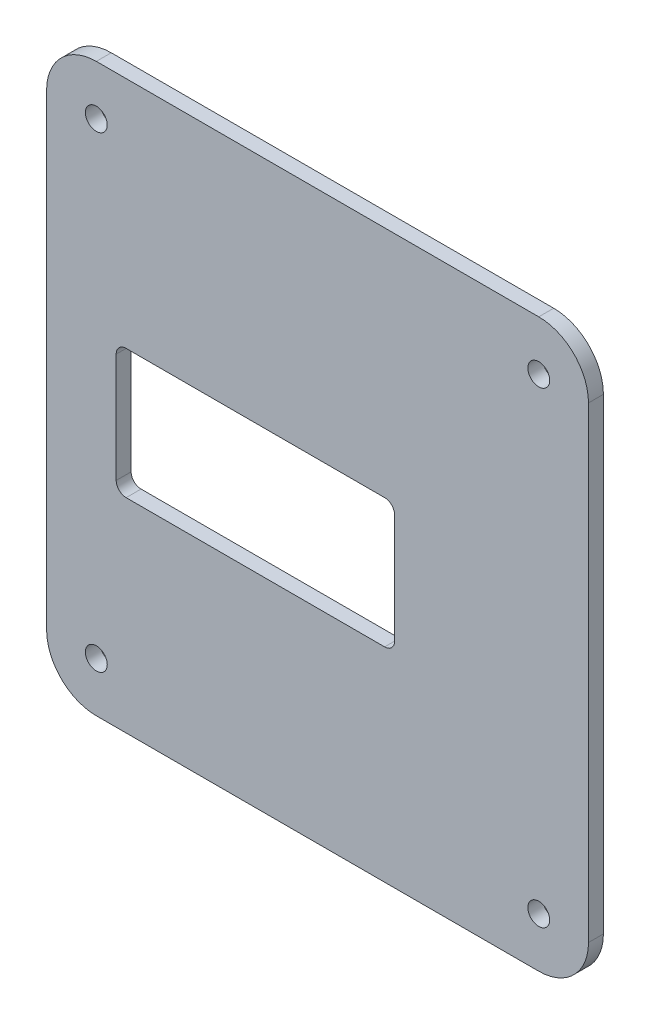
SolidWorks part; units mm, degrees
ref_plane "前视基准面" through (0, 0, 0) normal (0, 0, 1) x (1, 0, 0)
ref_plane "上视基准面" through (0, 0, 0) normal (0, 1, 0) x (1, 0, 0)
ref_plane "右视基准面" through (0, 0, 0) normal (1, 0, 0) x (0, 0, -1)
sketch "草图1" plane through (0, 0, 0) normal (0, 0, 1) x (1, 0, 0)
  line L1 (0, 0) -> (109, 0)
  line L2 (0, 0) -> (0, -114)
  line L3 (0, -114) -> (109, -114)
  line L4 (109, 0) -> (109, -114)
  line L5 (14, -47) -> (70, -47)
  line L6 (14, -47) -> (14, -73)
  line L7 (14, -73) -> (70, -73)
  line L8 (70, -47) -> (70, -73)
  circle A0 centre (99, -10) radius 2.2
  circle A1 centre (99, -104) radius 2.2
  circle A2 centre (10, -10) radius 2.2
  circle A3 centre (10, -104) radius 2.2
  dimension "D3" = 10
  dimension "D4" = 10
  dimension "D11" = 89
  dimension "D1" = 109
  dimension "D2" = 114
  dimension "D7" = 56
  dimension "D8" = 26
  dimension "D9" = 47
  dimension "D10" = 14
  dimension "D5" = 2
  dimension "D6" = 2
extrude "凸台-拉伸1" add sketch "草图1" along normal blind 3
fillet "圆角2" radius 2 4 edges at (14, -73, 1.5) (14, -47, 1.5) (70, -47, 1.5) (70, -73, 1.5)
fillet "圆角3" radius 10 4 edges at (0, 0, 1.5) (0, -114, 1.5) (109, -114, 1.5) (109, 0, 1.5)
